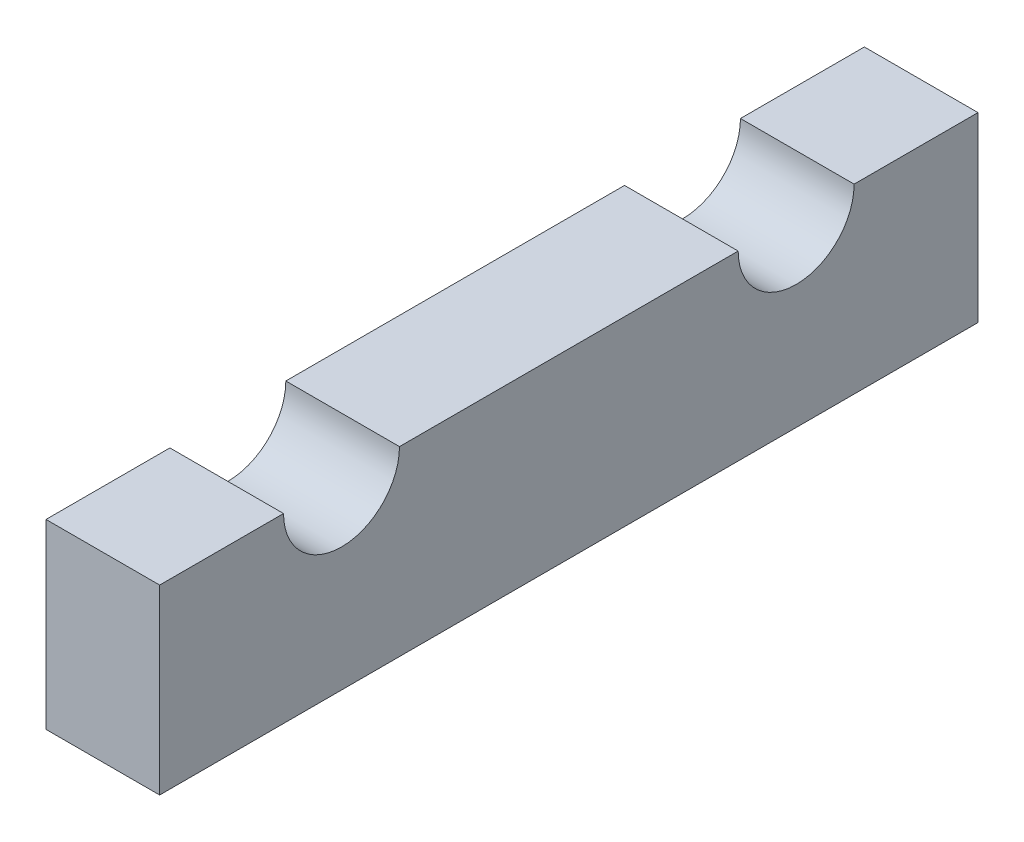
SolidWorks part; units mm, degrees
ref_plane "前视基准面" through (0, 0, 0) normal (0, 0, 1) x (1, 0, 0)
ref_plane "上视基准面" through (0, 0, 0) normal (0, 1, 0) x (1, 0, 0)
ref_plane "右视基准面" through (0, 0, 0) normal (1, 0, 0) x (0, 0, -1)
sketch "草图2" plane through (0, 0, 0) normal (1, 0, 0) x (0, 0, -1)
  line L0 (-7.45, 8) -> (7.45, 8)
  line L1 (-18, 0) -> (18, 0)
  line L2 (-18, 0) -> (-18, 8)
  line L3 (-18, 8) -> (-12.55, 8)
  line L4 (18, 0) -> (18, 8)
  line L5 (12.55, 8) -> (18, 8)
  arc A0 (7.45, 8) -> (12.55, 8) centre (10, 8) ccw
  arc A1 (-12.55, 8) -> (-7.45, 8) centre (-10, 8) ccw
  dimension "D4" = 5.1
  dimension "D5" = 5.1
  dimension "D1" = 8
  dimension "D2" = 36
  dimension "D3" = 18
  dimension "D6" = 20
  dimension "D7" = 10
extrude "凸台-拉伸1" add sketch "草图2" along normal blind 5
